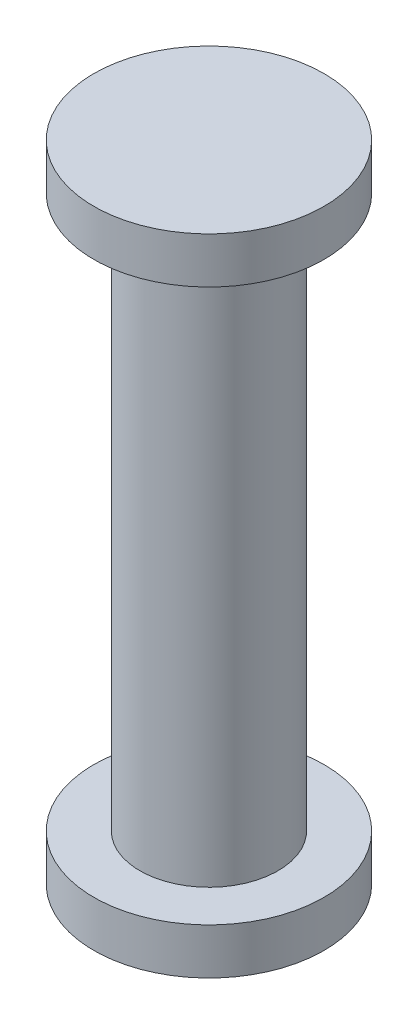
SolidWorks part; units mm, degrees
ref_plane "Front Plane" through (0, 0, 0) normal (0, 0, 1) x (1, 0, 0)
ref_plane "Top Plane" through (0, 0, 0) normal (0, 1, 0) x (1, 0, 0)
ref_plane "Right Plane" through (0, 0, 0) normal (1, 0, 0) x (0, 0, -1)
sketch "Sketch1" plane through (0, 0, 0) normal (0, 0, 1) x (1, 0, 0)
  line L0 (0, 0) -> (0, 14)
  line L1 (0, 14) -> (-2.5, 14)
  line L2 (-2.5, 14) -> (-2.5, 13)
  line L3 (-2.5, 13) -> (-1.5, 13)
  line L4 (-1.5, 13) -> (-1.5, 1)
  line L5 (-1.5, 1) -> (-2.5, 1)
  line L6 (-2.5, 1) -> (-2.5, 0)
  line L7 (-2.5, 0) -> (0, 0)
  dimension "D1" = 14
  dimension "D2" = 2.5
  dimension "D3" = 1.5
  dimension "D5" = 1
revolve "Revolve1" add sketch "Sketch1" angle 360 about L0
